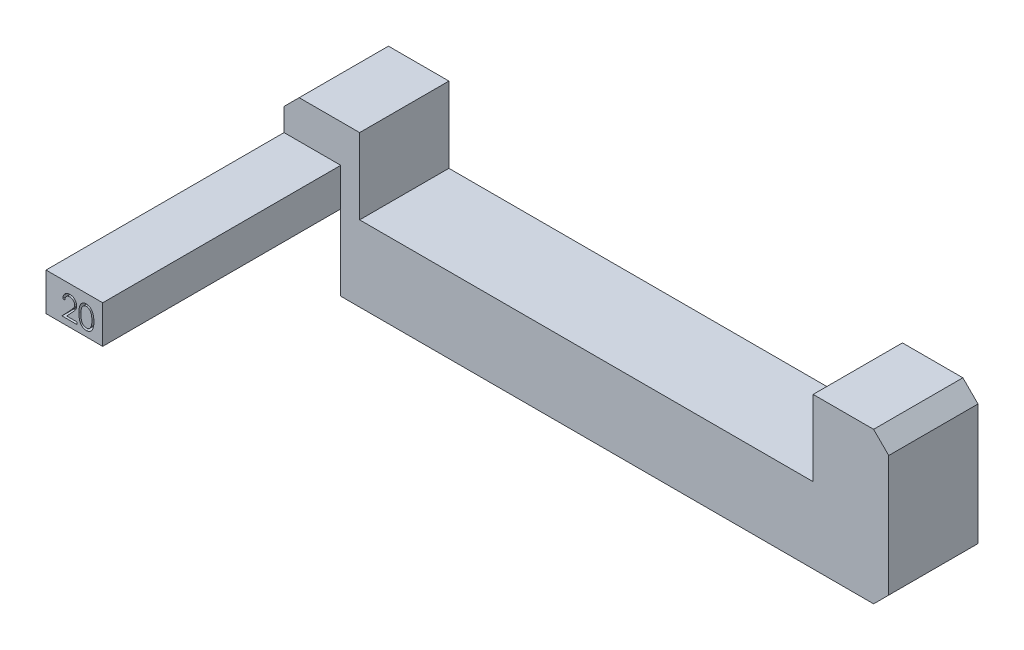
SolidWorks part; units mm, degrees
ref_plane "Front Plane" through (0, 0, 0) normal (0, 0, 1) x (1, 0, 0)
ref_plane "Top Plane" through (0, 0, 0) normal (0, 1, 0) x (1, 0, 0)
ref_plane "Right Plane" through (0, 0, 0) normal (1, 0, 0) x (0, 0, -1)
sketch "Sketch1" plane through (0, 0, 0) normal (0, 0, 1) x (1, 0, 0)
  line L1 (0, 0) -> (-101.6, 0)
  line L2 (0, 0) -> (0, 25.4)
  line L3 (0, 25.4) -> (-101.6, 25.4)
  line L4 (-101.6, 0) -> (-101.6, 25.4)
  line L5 (-12.7, 25.4) -> (-88.9, 25.4)
  line L6 (-12.7, 25.4) -> (-12.7, 12.7)
  line L7 (-12.7, 12.7) -> (-88.9, 12.7)
  line L8 (-88.9, 25.4) -> (-88.9, 12.7)
  point P9 (-50.8, 25.4)
  point P10 (-50.8, 12.7)
  dimension "D1" = 101.6
  dimension "D2" = 25.4
  dimension "D3" = 12.7
  dimension "D4" = 12.7
extrude "Boss-Extrude1" add sketch "Sketch1" along normal blind 15 contours L8 L3 L4 L1 L2 L6 L7
sketch "Sketch2" plane through (0, 0, 15) normal (0, 0, 1) x (1, 0, 0)
  line L0 (-101.6, 0) -> (-101.6, 25.4) construction
  line L1 (-101.6, 12.7) -> (-92.075, 12.7)
  line L2 (-101.6, 12.7) -> (-101.6, 19.05)
  line L3 (-101.6, 19.05) -> (-92.075, 19.05)
  line L4 (-92.075, 12.7) -> (-92.075, 19.05)
  line L5 (0, 0) -> (-101.6, 0) construction
  dimension "D1" = 9.525
  dimension "D2" = 6.35
  dimension "D3" = 12.7
extrude "Boss-Extrude2" add sketch "Sketch2" along normal blind 40
sketch "Sketch3" plane through (0, 0, 55) normal (0, 0, 1) x (1, 0, 0)
  line L0 (-101.6, 19.05) -> (-101.6, 12.7) construction
  line L2 (-101.6, 12.7) -> (-92.075, 12.7) construction
  text T0 "20" font "Century Gothic" height in points 14
  dimension "D1" = 2.54
  dimension "D2" = 1.016
extrude "Cut-Extrude1" cut sketch "Sketch3" against normal blind 2
chamfer "Chamfer1" distance 2.54 angle 45 4 edges at (0, 0, 7.5) (-101.6, 0, 7.5) (0, 25.4, 7.5) (-101.6, 25.4, 7.5)
sketch "Sketch4" plane through (0, 0, 15) normal (0, 0, 1) x (1, 0, 0)
  line L0 (-101.6, 2.54) -> (-101.6, 12.7) construction
  line L1 (-92.075, 12.7) -> (-101.6, 12.7)
  line L2 (-92.075, 12.7) -> (-92.075, 0)
  line L3 (-92.075, 0) -> (-101.6, 0)
  line L4 (-101.6, 12.7) -> (-101.6, 0)
  line L5 (-2.54, 0) -> (-99.06, 0) construction
extrude "Cut-Extrude2" cut sketch "Sketch4" against normal through all
